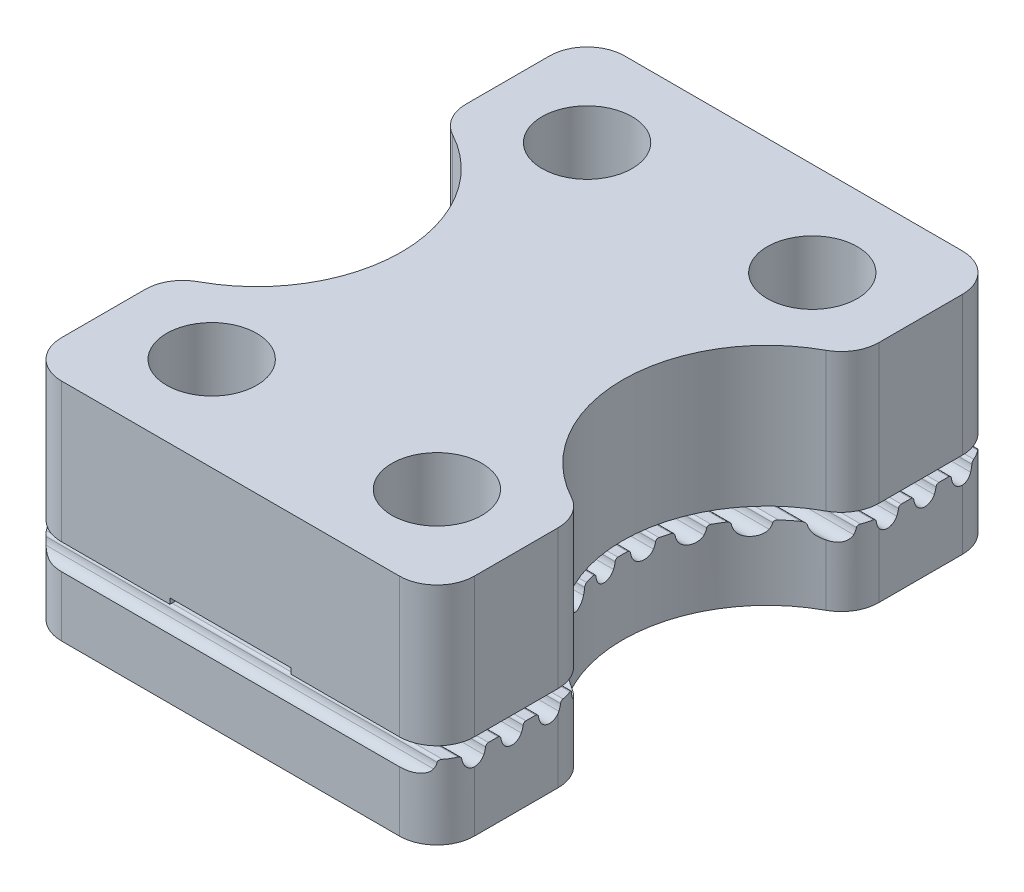
SolidWorks part; units mm, degrees
ref_plane "Front Plane" through (0, 0, 0) normal (0, 0, 1) x (1, 0, 0)
ref_plane "Top Plane" through (0, 0, 0) normal (0, 1, 0) x (1, 0, 0)
ref_plane "Right Plane" through (0, 0, 0) normal (1, 0, 0) x (0, 0, -1)
sketch "Sketch1" plane through (0, 0, 0) normal (0, 1, 0) x (1, 0, 0)
  line L0 (0, 0) -> (0, 15) construction
  line L1 (-11, -15) -> (11, -15)
  line L2 (-11, -15) -> (-11, -7.25)
  line L3 (-11, 15) -> (11, 15)
  line L4 (11, -15) -> (11, -7.25)
  line L5 (-11, -15) -> (11, 15) construction
  line L6 (-11, 15) -> (11, -15) construction
  line L7 (0, 0) -> (5.8937, 0) construction
  line L8 (-3.125, 15) -> (-3.125, -15) construction
  line L9 (3.125, 15) -> (3.125, -15) construction
  line L10 (-11, 7.25) -> (-11, 15)
  line L11 (11, 7.25) -> (11, 15)
  circle A0 centre (-6, 10) radius 2 construction
  arc A1 (-11, -7.25) -> (-11, 7.25) centre (-13.5937, 0) ccw
  arc A2 (11, -7.25) -> (11, 7.25) centre (13.5937, 0) cw
  point P0 (0, 0)
  point P5 (-6, 10)
  point P6 (6, 10)
  point P8 (6, -10)
  point P9 (-6, -10)
  dimension "D1" = 20
  dimension "D3" = 4
  dimension "D5" = 22
  dimension "D7" = 7.7
  dimension "D2" = 12
  dimension "D4" = 6.25
  dimension "D6" = 30
  dimension "D8" = 14.5
extrude "Boss-Extrude1" add sketch "Sketch1" against normal blind 12
sketch "Sketch2" plane through (0, 0, 0) normal (1, 0, 0) x (0, 0, -1)
  line L0 (-15, -7.42) -> (15, -7.42)
  line L1 (-15, -12) -> (-15, 0) construction
  line L2 (15, -12) -> (15, 0) construction
  line L3 (7.25, 0) -> (15, 0) construction
  line L4 (-14, -7.42) -> (-14, -10.333) construction
  line L5 (-14.2598, -8.05) -> (-14, -8.05)
  line L6 (-16, -10.333) -> (-16, -7.42) construction
  line L7 (-15.7402, -8.05) -> (-16, -8.05)
  line L8 (-13.7402, -8.05) -> (-14, -8.05)
  line L36 (-15, -7.42) -> (-16, -7.42)
  line L37 (-16, -7.42) -> (-16, -8.05)
  line L38 (15, -7.42) -> (14, -7.42)
  line L40 (-12.2598, -8.05) -> (-12, -8.05) [skipped]
  line L41 (-11.7402, -8.05) -> (-12, -8.05) [skipped]
  line L42 (-10.2598, -8.05) -> (-10, -8.05) [skipped]
  line L43 (-9.7402, -8.05) -> (-10, -8.05) [skipped]
  line L44 (-8.2598, -8.05) -> (-8, -8.05) [skipped]
  line L45 (-7.7402, -8.05) -> (-8, -8.05) [skipped]
  line L46 (-6.2598, -8.05) -> (-6, -8.05) [skipped]
  line L47 (-5.7402, -8.05) -> (-6, -8.05) [skipped]
  line L48 (-4.2598, -8.05) -> (-4, -8.05) [skipped]
  line L49 (-3.7402, -8.05) -> (-4, -8.05) [skipped]
  line L50 (-2.2598, -8.05) -> (-2, -8.05) [skipped]
  line L51 (-1.7402, -8.05) -> (-2, -8.05) [skipped]
  line L52 (-0.2598, -8.05) -> (0, -8.05) [skipped]
  line L53 (0.2598, -8.05) -> (0, -8.05) [skipped]
  line L54 (1.7402, -8.05) -> (2, -8.05) [skipped]
  line L55 (2.2598, -8.05) -> (2, -8.05) [skipped]
  line L56 (3.7402, -8.05) -> (4, -8.05) [skipped]
  line L57 (4.2598, -8.05) -> (4, -8.05) [skipped]
  line L58 (5.7402, -8.05) -> (6, -8.05) [skipped]
  line L59 (6.2598, -8.05) -> (6, -8.05) [skipped]
  line L60 (7.7402, -8.05) -> (8, -8.05) [skipped]
  line L61 (8.2598, -8.05) -> (8, -8.05) [skipped]
  line L62 (9.7402, -8.05) -> (10, -8.05) [skipped]
  line L63 (10.2598, -8.05) -> (10, -8.05) [skipped]
  line L64 (11.7402, -8.05) -> (12, -8.05) [skipped]
  line L65 (12.2598, -8.05) -> (12, -8.05) [skipped]
  line L66 (13.7402, -8.05) -> (14, -8.05) [skipped]
  line L67 (-13.7402, -8.05) -> (-14, -8.05)
  line L68 (-12.2598, -8.05) -> (-12, -8.05)
  line L69 (-11.7402, -8.05) -> (-12, -8.05)
  line L70 (-10.2598, -8.05) -> (-10, -8.05)
  line L71 (-9.7402, -8.05) -> (-10, -8.05)
  line L72 (-8.2598, -8.05) -> (-8, -8.05)
  line L73 (-7.7402, -8.05) -> (-8, -8.05)
  line L74 (-6.2598, -8.05) -> (-6, -8.05)
  line L75 (-5.7402, -8.05) -> (-6, -8.05)
  line L76 (-4.2598, -8.05) -> (-4, -8.05)
  line L77 (-3.7402, -8.05) -> (-4, -8.05)
  line L78 (-2.2598, -8.05) -> (-2, -8.05)
  line L79 (-1.7402, -8.05) -> (-2, -8.05)
  line L80 (-0.2598, -8.05) -> (0, -8.05)
  line L81 (0.2598, -8.05) -> (0, -8.05)
  line L82 (1.7402, -8.05) -> (2, -8.05)
  line L83 (2.2598, -8.05) -> (2, -8.05)
  line L84 (3.7402, -8.05) -> (4, -8.05)
  line L85 (4.2598, -8.05) -> (4, -8.05)
  line L86 (5.7402, -8.05) -> (6, -8.05)
  line L87 (6.2598, -8.05) -> (6, -8.05)
  line L88 (7.7402, -8.05) -> (8, -8.05)
  line L89 (8.2598, -8.05) -> (8, -8.05)
  line L90 (9.7402, -8.05) -> (10, -8.05)
  line L91 (10.2598, -8.05) -> (10, -8.05)
  line L92 (11.7402, -8.05) -> (12, -8.05)
  line L93 (12.2598, -8.05) -> (12, -8.05)
  line L94 (13.7402, -8.05) -> (14, -8.05)
  line L95 (14.2598, -8.05) -> (14, -8.05)
  line L96 (15.7402, -8.05) -> (16, -8.05)
  line L97 (16, -8.05) -> (15, -7.42)
  arc A0 (-15.4989, -8.4882) -> (-14.5011, -8.4882) centre (-15, -8.245) ccw
  arc A1 (-15.4989, -8.4882) -> (-15.5915, -8.1804) centre (-14.6, -8.05) cw
  arc A2 (-14.5011, -8.4882) -> (-14.4085, -8.1804) centre (-15.4, -8.05) ccw
  arc A3 (-14.4085, -8.1804) -> (-14.2598, -8.05) centre (-14.2598, -8.2) cw
  arc A4 (-15.5915, -8.1804) -> (-15.7402, -8.05) centre (-15.7402, -8.2) ccw
  arc A75 (-13.4989, -8.4882) -> (-13.5915, -8.1804) centre (-12.6, -8.05) cw [skipped]
  arc A76 (-13.4989, -8.4882) -> (-12.5011, -8.4882) centre (-13, -8.245) ccw [skipped]
  arc A77 (-12.5011, -8.4882) -> (-12.4085, -8.1804) centre (-13.4, -8.05) ccw [skipped]
  arc A78 (-12.4085, -8.1804) -> (-12.2598, -8.05) centre (-12.2598, -8.2) cw [skipped]
  arc A79 (-11.5915, -8.1804) -> (-11.7402, -8.05) centre (-11.7402, -8.2) ccw [skipped]
  arc A80 (-11.4989, -8.4882) -> (-11.5915, -8.1804) centre (-10.6, -8.05) cw [skipped]
  arc A81 (-11.4989, -8.4882) -> (-10.5011, -8.4882) centre (-11, -8.245) ccw [skipped]
  arc A82 (-10.5011, -8.4882) -> (-10.4085, -8.1804) centre (-11.4, -8.05) ccw [skipped]
  arc A83 (-10.4085, -8.1804) -> (-10.2598, -8.05) centre (-10.2598, -8.2) cw [skipped]
  arc A84 (-9.5915, -8.1804) -> (-9.7402, -8.05) centre (-9.7402, -8.2) ccw [skipped]
  arc A85 (-9.4989, -8.4882) -> (-9.5915, -8.1804) centre (-8.6, -8.05) cw [skipped]
  arc A86 (-13.5915, -8.1804) -> (-13.7402, -8.05) centre (-13.7402, -8.2) ccw [skipped]
  arc A87 (-9.4989, -8.4882) -> (-8.5011, -8.4882) centre (-9, -8.245) ccw [skipped]
  arc A88 (-8.5011, -8.4882) -> (-8.4085, -8.1804) centre (-9.4, -8.05) ccw [skipped]
  arc A89 (-8.4085, -8.1804) -> (-8.2598, -8.05) centre (-8.2598, -8.2) cw [skipped]
  arc A90 (-7.5915, -8.1804) -> (-7.7402, -8.05) centre (-7.7402, -8.2) ccw [skipped]
  arc A91 (-7.4989, -8.4882) -> (-7.5915, -8.1804) centre (-6.6, -8.05) cw [skipped]
  arc A92 (-7.4989, -8.4882) -> (-6.5011, -8.4882) centre (-7, -8.245) ccw [skipped]
  arc A93 (-6.5011, -8.4882) -> (-6.4085, -8.1804) centre (-7.4, -8.05) ccw [skipped]
  arc A94 (-6.4085, -8.1804) -> (-6.2598, -8.05) centre (-6.2598, -8.2) cw [skipped]
  arc A95 (-5.5915, -8.1804) -> (-5.7402, -8.05) centre (-5.7402, -8.2) ccw [skipped]
  arc A96 (-5.4989, -8.4882) -> (-5.5915, -8.1804) centre (-4.6, -8.05) cw [skipped]
  arc A97 (-5.4989, -8.4882) -> (-4.5011, -8.4882) centre (-5, -8.245) ccw [skipped]
  arc A98 (-4.5011, -8.4882) -> (-4.4085, -8.1804) centre (-5.4, -8.05) ccw [skipped]
  arc A99 (-4.4085, -8.1804) -> (-4.2598, -8.05) centre (-4.2598, -8.2) cw [skipped]
  arc A100 (-3.5915, -8.1804) -> (-3.7402, -8.05) centre (-3.7402, -8.2) ccw [skipped]
  arc A101 (-3.4989, -8.4882) -> (-3.5915, -8.1804) centre (-2.6, -8.05) cw [skipped]
  arc A102 (-3.4989, -8.4882) -> (-2.5011, -8.4882) centre (-3, -8.245) ccw [skipped]
  arc A103 (-2.5011, -8.4882) -> (-2.4085, -8.1804) centre (-3.4, -8.05) ccw [skipped]
  arc A104 (-2.4085, -8.1804) -> (-2.2598, -8.05) centre (-2.2598, -8.2) cw [skipped]
  arc A105 (-1.5915, -8.1804) -> (-1.7402, -8.05) centre (-1.7402, -8.2) ccw [skipped]
  arc A106 (-1.4989, -8.4882) -> (-1.5915, -8.1804) centre (-0.6, -8.05) cw [skipped]
  arc A107 (-1.4989, -8.4882) -> (-0.5011, -8.4882) centre (-1, -8.245) ccw [skipped]
  arc A108 (-0.5011, -8.4882) -> (-0.4085, -8.1804) centre (-1.4, -8.05) ccw [skipped]
  arc A109 (-0.4085, -8.1804) -> (-0.2598, -8.05) centre (-0.2598, -8.2) cw [skipped]
  arc A110 (0.4085, -8.1804) -> (0.2598, -8.05) centre (0.2598, -8.2) ccw [skipped]
  arc A111 (0.5011, -8.4882) -> (0.4085, -8.1804) centre (1.4, -8.05) cw [skipped]
  arc A112 (0.5011, -8.4882) -> (1.4989, -8.4882) centre (1, -8.245) ccw [skipped]
  arc A113 (1.4989, -8.4882) -> (1.5915, -8.1804) centre (0.6, -8.05) ccw [skipped]
  arc A114 (1.5915, -8.1804) -> (1.7402, -8.05) centre (1.7402, -8.2) cw [skipped]
  arc A115 (2.4085, -8.1804) -> (2.2598, -8.05) centre (2.2598, -8.2) ccw [skipped]
  arc A116 (2.5011, -8.4882) -> (2.4085, -8.1804) centre (3.4, -8.05) cw [skipped]
  arc A117 (2.5011, -8.4882) -> (3.4989, -8.4882) centre (3, -8.245) ccw [skipped]
  arc A118 (3.4989, -8.4882) -> (3.5915, -8.1804) centre (2.6, -8.05) ccw [skipped]
  arc A119 (3.5915, -8.1804) -> (3.7402, -8.05) centre (3.7402, -8.2) cw [skipped]
  arc A120 (4.4085, -8.1804) -> (4.2598, -8.05) centre (4.2598, -8.2) ccw [skipped]
  arc A121 (4.5011, -8.4882) -> (4.4085, -8.1804) centre (5.4, -8.05) cw [skipped]
  arc A122 (4.5011, -8.4882) -> (5.4989, -8.4882) centre (5, -8.245) ccw [skipped]
  arc A123 (5.4989, -8.4882) -> (5.5915, -8.1804) centre (4.6, -8.05) ccw [skipped]
  arc A124 (5.5915, -8.1804) -> (5.7402, -8.05) centre (5.7402, -8.2) cw [skipped]
  arc A125 (6.4085, -8.1804) -> (6.2598, -8.05) centre (6.2598, -8.2) ccw [skipped]
  arc A126 (6.5011, -8.4882) -> (6.4085, -8.1804) centre (7.4, -8.05) cw [skipped]
  arc A127 (6.5011, -8.4882) -> (7.4989, -8.4882) centre (7, -8.245) ccw [skipped]
  arc A128 (7.4989, -8.4882) -> (7.5915, -8.1804) centre (6.6, -8.05) ccw [skipped]
  arc A129 (7.5915, -8.1804) -> (7.7402, -8.05) centre (7.7402, -8.2) cw [skipped]
  arc A130 (8.4085, -8.1804) -> (8.2598, -8.05) centre (8.2598, -8.2) ccw [skipped]
  arc A131 (8.5011, -8.4882) -> (8.4085, -8.1804) centre (9.4, -8.05) cw [skipped]
  arc A132 (8.5011, -8.4882) -> (9.4989, -8.4882) centre (9, -8.245) ccw [skipped]
  arc A133 (9.4989, -8.4882) -> (9.5915, -8.1804) centre (8.6, -8.05) ccw [skipped]
  arc A134 (9.5915, -8.1804) -> (9.7402, -8.05) centre (9.7402, -8.2) cw [skipped]
  arc A135 (10.4085, -8.1804) -> (10.2598, -8.05) centre (10.2598, -8.2) ccw [skipped]
  arc A136 (10.5011, -8.4882) -> (10.4085, -8.1804) centre (11.4, -8.05) cw [skipped]
  arc A137 (10.5011, -8.4882) -> (11.4989, -8.4882) centre (11, -8.245) ccw [skipped]
  arc A138 (11.4989, -8.4882) -> (11.5915, -8.1804) centre (10.6, -8.05) ccw [skipped]
  arc A139 (11.5915, -8.1804) -> (11.7402, -8.05) centre (11.7402, -8.2) cw [skipped]
  arc A140 (12.4085, -8.1804) -> (12.2598, -8.05) centre (12.2598, -8.2) ccw [skipped]
  arc A141 (12.5011, -8.4882) -> (12.4085, -8.1804) centre (13.4, -8.05) cw [skipped]
  arc A142 (12.5011, -8.4882) -> (13.4989, -8.4882) centre (13, -8.245) ccw [skipped]
  arc A143 (13.4989, -8.4882) -> (13.5915, -8.1804) centre (12.6, -8.05) ccw [skipped]
  arc A144 (13.5915, -8.1804) -> (13.7402, -8.05) centre (13.7402, -8.2) cw [skipped]
  arc A145 (-13.5915, -8.1804) -> (-13.7402, -8.05) centre (-13.7402, -8.2) ccw
  arc A146 (-13.4989, -8.4882) -> (-13.5915, -8.1804) centre (-12.6, -8.05) cw
  arc A147 (-13.4989, -8.4882) -> (-12.5011, -8.4882) centre (-13, -8.245) ccw
  arc A148 (-12.5011, -8.4882) -> (-12.4085, -8.1804) centre (-13.4, -8.05) ccw
  arc A149 (-12.4085, -8.1804) -> (-12.2598, -8.05) centre (-12.2598, -8.2) cw
  arc A150 (-11.5915, -8.1804) -> (-11.7402, -8.05) centre (-11.7402, -8.2) ccw
  arc A151 (-11.4989, -8.4882) -> (-11.5915, -8.1804) centre (-10.6, -8.05) cw
  arc A152 (-11.4989, -8.4882) -> (-10.5011, -8.4882) centre (-11, -8.245) ccw
  arc A153 (-10.5011, -8.4882) -> (-10.4085, -8.1804) centre (-11.4, -8.05) ccw
  arc A154 (-10.4085, -8.1804) -> (-10.2598, -8.05) centre (-10.2598, -8.2) cw
  arc A155 (-9.5915, -8.1804) -> (-9.7402, -8.05) centre (-9.7402, -8.2) ccw
  arc A156 (-9.4989, -8.4882) -> (-9.5915, -8.1804) centre (-8.6, -8.05) cw
  arc A157 (-9.4989, -8.4882) -> (-8.5011, -8.4882) centre (-9, -8.245) ccw
  arc A158 (-8.5011, -8.4882) -> (-8.4085, -8.1804) centre (-9.4, -8.05) ccw
  arc A159 (-8.4085, -8.1804) -> (-8.2598, -8.05) centre (-8.2598, -8.2) cw
  arc A160 (-7.5915, -8.1804) -> (-7.7402, -8.05) centre (-7.7402, -8.2) ccw
  arc A161 (-7.4989, -8.4882) -> (-7.5915, -8.1804) centre (-6.6, -8.05) cw
  arc A162 (-7.4989, -8.4882) -> (-6.5011, -8.4882) centre (-7, -8.245) ccw
  arc A163 (-6.5011, -8.4882) -> (-6.4085, -8.1804) centre (-7.4, -8.05) ccw
  arc A164 (-6.4085, -8.1804) -> (-6.2598, -8.05) centre (-6.2598, -8.2) cw
  arc A165 (-5.5915, -8.1804) -> (-5.7402, -8.05) centre (-5.7402, -8.2) ccw
  arc A166 (-5.4989, -8.4882) -> (-5.5915, -8.1804) centre (-4.6, -8.05) cw
  arc A167 (-5.4989, -8.4882) -> (-4.5011, -8.4882) centre (-5, -8.245) ccw
  arc A168 (-4.5011, -8.4882) -> (-4.4085, -8.1804) centre (-5.4, -8.05) ccw
  arc A169 (-4.4085, -8.1804) -> (-4.2598, -8.05) centre (-4.2598, -8.2) cw
  arc A170 (-3.5915, -8.1804) -> (-3.7402, -8.05) centre (-3.7402, -8.2) ccw
  arc A171 (-3.4989, -8.4882) -> (-3.5915, -8.1804) centre (-2.6, -8.05) cw
  arc A172 (-3.4989, -8.4882) -> (-2.5011, -8.4882) centre (-3, -8.245) ccw
  arc A173 (-2.5011, -8.4882) -> (-2.4085, -8.1804) centre (-3.4, -8.05) ccw
  arc A174 (-2.4085, -8.1804) -> (-2.2598, -8.05) centre (-2.2598, -8.2) cw
  arc A175 (-1.5915, -8.1804) -> (-1.7402, -8.05) centre (-1.7402, -8.2) ccw
  arc A176 (-1.4989, -8.4882) -> (-1.5915, -8.1804) centre (-0.6, -8.05) cw
  arc A177 (-1.4989, -8.4882) -> (-0.5011, -8.4882) centre (-1, -8.245) ccw
  arc A178 (-0.5011, -8.4882) -> (-0.4085, -8.1804) centre (-1.4, -8.05) ccw
  arc A179 (-0.4085, -8.1804) -> (-0.2598, -8.05) centre (-0.2598, -8.2) cw
  arc A180 (0.4085, -8.1804) -> (0.2598, -8.05) centre (0.2598, -8.2) ccw
  arc A181 (0.5011, -8.4882) -> (0.4085, -8.1804) centre (1.4, -8.05) cw
  arc A182 (0.5011, -8.4882) -> (1.4989, -8.4882) centre (1, -8.245) ccw
  arc A183 (1.4989, -8.4882) -> (1.5915, -8.1804) centre (0.6, -8.05) ccw
  arc A184 (1.5915, -8.1804) -> (1.7402, -8.05) centre (1.7402, -8.2) cw
  arc A185 (2.4085, -8.1804) -> (2.2598, -8.05) centre (2.2598, -8.2) ccw
  arc A186 (2.5011, -8.4882) -> (2.4085, -8.1804) centre (3.4, -8.05) cw
  arc A187 (2.5011, -8.4882) -> (3.4989, -8.4882) centre (3, -8.245) ccw
  arc A188 (3.4989, -8.4882) -> (3.5915, -8.1804) centre (2.6, -8.05) ccw
  arc A189 (3.5915, -8.1804) -> (3.7402, -8.05) centre (3.7402, -8.2) cw
  arc A190 (4.4085, -8.1804) -> (4.2598, -8.05) centre (4.2598, -8.2) ccw
  arc A191 (4.5011, -8.4882) -> (4.4085, -8.1804) centre (5.4, -8.05) cw
  arc A192 (4.5011, -8.4882) -> (5.4989, -8.4882) centre (5, -8.245) ccw
  arc A193 (5.4989, -8.4882) -> (5.5915, -8.1804) centre (4.6, -8.05) ccw
  arc A194 (5.5915, -8.1804) -> (5.7402, -8.05) centre (5.7402, -8.2) cw
  arc A195 (6.4085, -8.1804) -> (6.2598, -8.05) centre (6.2598, -8.2) ccw
  arc A196 (6.5011, -8.4882) -> (6.4085, -8.1804) centre (7.4, -8.05) cw
  arc A197 (6.5011, -8.4882) -> (7.4989, -8.4882) centre (7, -8.245) ccw
  arc A198 (7.4989, -8.4882) -> (7.5915, -8.1804) centre (6.6, -8.05) ccw
  arc A199 (7.5915, -8.1804) -> (7.7402, -8.05) centre (7.7402, -8.2) cw
  arc A200 (8.4085, -8.1804) -> (8.2598, -8.05) centre (8.2598, -8.2) ccw
  arc A201 (8.5011, -8.4882) -> (8.4085, -8.1804) centre (9.4, -8.05) cw
  arc A202 (8.5011, -8.4882) -> (9.4989, -8.4882) centre (9, -8.245) ccw
  arc A203 (9.4989, -8.4882) -> (9.5915, -8.1804) centre (8.6, -8.05) ccw
  arc A204 (9.5915, -8.1804) -> (9.7402, -8.05) centre (9.7402, -8.2) cw
  arc A205 (10.4085, -8.1804) -> (10.2598, -8.05) centre (10.2598, -8.2) ccw
  arc A206 (10.5011, -8.4882) -> (10.4085, -8.1804) centre (11.4, -8.05) cw
  arc A207 (10.5011, -8.4882) -> (11.4989, -8.4882) centre (11, -8.245) ccw
  arc A208 (11.4989, -8.4882) -> (11.5915, -8.1804) centre (10.6, -8.05) ccw
  arc A209 (11.5915, -8.1804) -> (11.7402, -8.05) centre (11.7402, -8.2) cw
  arc A210 (12.4085, -8.1804) -> (12.2598, -8.05) centre (12.2598, -8.2) ccw
  arc A211 (12.5011, -8.4882) -> (12.4085, -8.1804) centre (13.4, -8.05) cw
  arc A212 (12.5011, -8.4882) -> (13.4989, -8.4882) centre (13, -8.245) ccw
  arc A213 (13.4989, -8.4882) -> (13.5915, -8.1804) centre (12.6, -8.05) ccw
  arc A214 (13.5915, -8.1804) -> (13.7402, -8.05) centre (13.7402, -8.2) cw
  arc A215 (14.4085, -8.1804) -> (14.2598, -8.05) centre (14.2598, -8.2) ccw
  arc A216 (14.5011, -8.4882) -> (14.4085, -8.1804) centre (15.4, -8.05) cw
  arc A217 (14.5011, -8.4882) -> (15.4989, -8.4882) centre (15, -8.245) ccw
  arc A218 (15.4989, -8.4882) -> (15.5915, -8.1804) centre (14.6, -8.05) ccw
  arc A219 (15.5915, -8.1804) -> (15.7402, -8.05) centre (15.7402, -8.2) cw
  point P11 (-14.6, -8.05)
  point P20 (-14.4, -8.05)
  dimension "D2" = 0.555
  dimension "D3" = 1.38
  dimension "D5" = 1
  dimension "D8" = 0.15
  dimension "D1" = 7.42
  dimension "D4" = 0.4
  dimension "D6" = 0.63
  dimension "D7" = 1
  dimension "D9" = 1
  dimension "D11" = 16
  dimension "D10" = 15
extrude "Cut-Extrude1" cut sketch "Sketch2" against normal through all both and the other way through all contours A218 A219 L96 L97 L0 L36 L37 L7 A4 A1 A0 A2 A3 L5 L8 A145 A146 A147 A148 A149 L68 L69 A150 A151 A152 A153 A154 L70 L71 A155 A156 A157 A158 A159 L72 L73 A160 A161 A162 A163 A164 L74 L75 A165 A166 A167 A168 A169 L76 L77
hole_wizard "M4 Clearance Hole1" positions "Sketch3" profile "Sketch4" hole size "M4" standard "ANSI Metric" end condition through all
sketch "Sketch3" plane through (0, 0, 0) normal (0, 1, 0) x (1, 0, 0)
  point P0 (6, -10)
  point P3 (-6, -10)
  point P6 (6, 10)
  point P9 (-6, 10)
sketch "Sketch4" plane through (6, 0, 10) normal (1, 0, 0) x (0, 0, 1)
  line L0 (0, 0) -> (0, 12)
  line L1 (0, 12) -> (2.4, 12)
  line L2 (2.4, 12) -> (2.4, 0)
  line L5 (2.4, 0) -> (0, 0)
  line L11 (0, -6.35) -> (0, 107.95) construction
  dimension "Thru Hole Dia." = 4.8
  dimension "Thru Hole Depth" = 12
sketch "Sketch5" plane through (0, 0, 0) normal (0, 0, 1) x (1, 0, 0)
  line L0 (-11, -7.42) -> (11, -7.42) construction
  line L1 (3.225, -7.42) -> (-3.225, -7.42)
  line L2 (3.225, -7.42) -> (3.225, -7.12)
  line L3 (3.225, -7.12) -> (-3.225, -7.12)
  line L4 (-3.225, -7.42) -> (-3.225, -7.12)
  point P6 (0, -7.12)
  dimension "D1" = 6.45
  dimension "D2" = 0.3
extrude "Cut-Extrude2" cut sketch "Sketch5" against normal through all both and the other way through all
fillet "Fillet1" radius 2 8 edges at (11, -3.71, -7.25) (-11, -3.71, 15) (-11, -3.71, 7.25) (-11, -3.71, -7.25) (-11, -3.71, -15) (11, -3.71, -15) (11, -3.71, 7.25) (11, -3.71, 15)
fillet "Fillet2" radius 2 8 edges at (11, -10.4, -15) (-11, -10.4, -15) (-11, -10.3703, -7.25) (-11, -10.3703, 7.25) (-11, -10.4, 15) (11, -10.3703, -7.25) (11, -10.3703, 7.25) (11, -10.4, 15)
